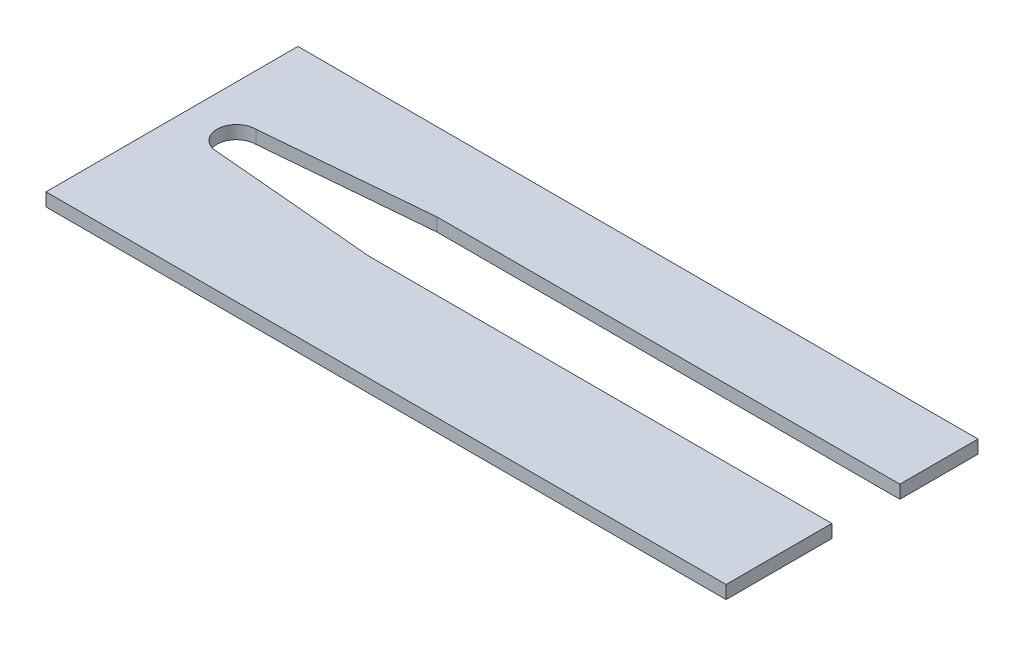
SolidWorks part; units mm, degrees
material "Rubber"
ref_plane "Front Plane" through (0, 0, 0) normal (0, 0, 1) x (1, 0, 0)
ref_plane "Top Plane" through (0, 0, 0) normal (0, 1, 0) x (1, 0, 0)
ref_plane "Right Plane" through (0, 0, 0) normal (1, 0, 0) x (0, 0, -1)
sketch "Sketch1" plane through (0, 0, 0) normal (0, 1, 0) x (1, 0, 0)
  line L1 (2.3213, 84.2903) -> (37.3213, 84.2903)
  line L2 (2.3213, 84.2903) -> (2.3213, 71.326)
  line L3 (2.3213, 71.326) -> (37.3213, 71.326)
  line L4 (37.3213, 84.2903) -> (37.3213, 71.326)
  dimension "D1" = 35
extrude "Boss-Extrude1" add sketch "Sketch1" along normal blind 0.675
sketch "Sketch2" plane through (0, 0.675, 0) normal (0, 1, 0) x (1, 0, 0)
  line L5 (13.5025, 76.768) -> (37.3213, 76.768)
  line L6 (4.9299, 78.518) -> (38.5708, 78.518) construction
  line L7 (37.3213, 71.326) -> (37.3213, 84.2903) construction
  line L13 (37.3213, 76.768) -> (37.3213, 78.518)
  line L14 (37.3213, 84.2903) -> (2.3213, 84.2903) construction
  line L15 (13.5025, 80.268) -> (37.3213, 80.268)
  line L16 (4.9299, 77.518) -> (13.5025, 76.768)
  line L17 (4.9299, 79.518) -> (13.5025, 80.268)
  line L18 (37.3213, 80.268) -> (37.3213, 78.518)
  arc A1 (4.9299, 79.518) -> (4.9299, 77.518) centre (4.9299, 78.518) ccw
  dimension "D3" = 2
  dimension "D4" = 175
  dimension "D1" = 5.7723
  dimension "D2" = 1.75
extrude "Cut-Extrude1" cut sketch "Sketch2" against normal blind 0.68
